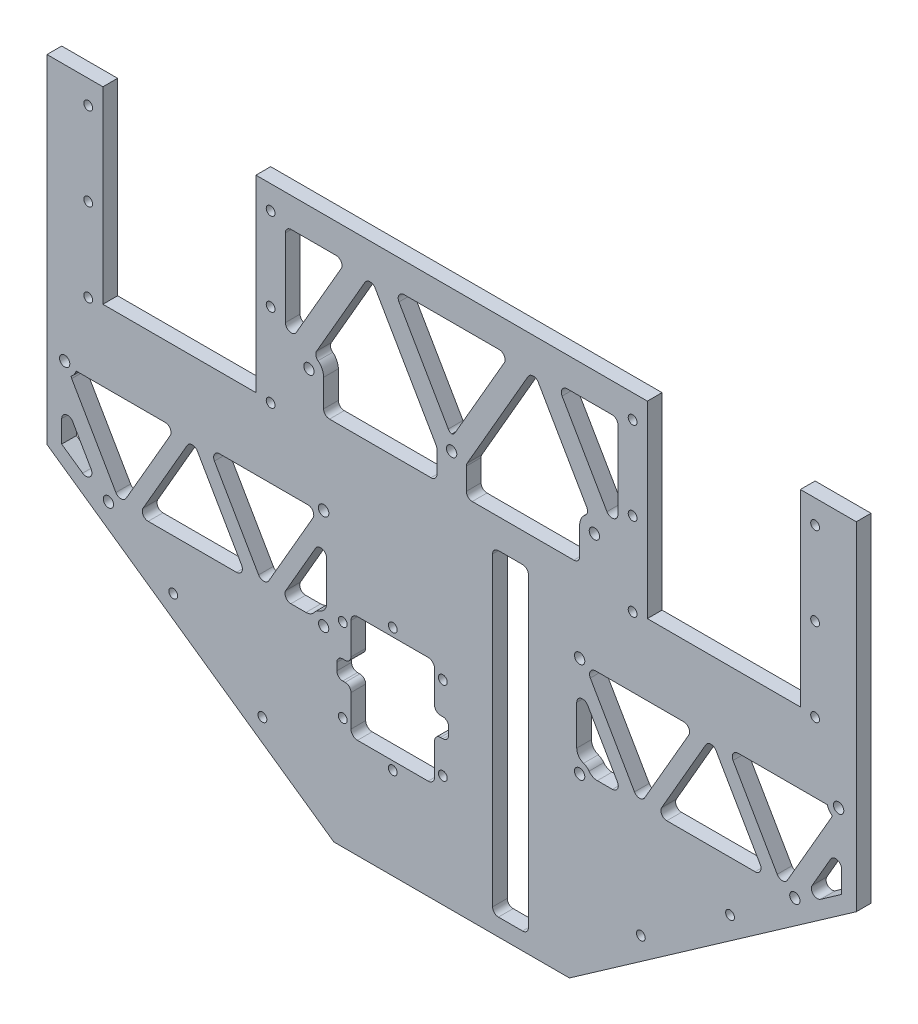
SolidWorks part; units mm, degrees
ref_plane "Front Plane" through (0, 0, 0) normal (0, 0, 1) x (1, 0, 0)
ref_plane "Top Plane" through (0, 0, 0) normal (0, 1, 0) x (1, 0, 0)
ref_plane "Right Plane" through (0, 0, 0) normal (1, 0, 0) x (0, 0, -1)
sketch "Model" plane through (0, 0, 0) normal (0, 0, 1) x (1, 0, 0)
  line L0 (25.9808, 54.5) -> (5.2679, 18.6244)
  line L1 (45.9002, 25.9986) -> (29.4449, 54.5)
  line L2 (43.5, 10.2107) -> (43.5, 19.5)
  line L3 (7, 8.2107) -> (41.5, 8.2107)
  line L4 (5, 10.2107) -> (5, 17.6244)
  line L5 (-56.5, 55.5) -> (-56.5, 29.1032)
  line L6 (-39.2598, 57.5) -> (-54.5, 57.5)
  line L7 (-52.7679, 28.1032) -> (-37.5278, 54.5)
  line L8 (-5, 10.2107) -> (-5, 17.6244)
  line L9 (-41.5, 8.2107) -> (-7, 8.2107)
  line L10 (-43.5, 10.2107) -> (-43.5, 19.5)
  line L11 (-45.9002, 25.9986) -> (-29.4449, 54.5)
  line L12 (-25.9808, 54.5) -> (-5.2679, 18.6244)
  line L13 (47.1188, -23.6806) -> (62.1299, -49.6806)
  line L14 (48.8509, -20.6806) -> (78.8731, -20.6806)
  line L15 (65.594, -49.6806) -> (80.6051, -23.6806)
  line L16 (49.5, -52.6806) -> (54.6244, -52.6806)
  line L17 (42.5, -46.6096) -> (42.5, -33.1447)
  line L18 (56.3564, -49.6806) -> (46.2321, -32.1447)
  line L19 (104.8538, -49.6806) -> (89.8427, -23.6806)
  line L20 (103.1218, -52.6806) -> (73.0996, -52.6806)
  line L21 (86.3786, -23.6806) -> (71.3675, -49.6806)
  line L22 (-71.3675, -49.6806) -> (-86.3786, -23.6806)
  line L23 (-103.1218, -52.6806) -> (-73.0996, -52.6806)
  line L24 (-104.8538, -49.6806) -> (-89.8427, -23.6806)
  line L25 (-110.6273, -49.6806) -> (-95.6162, -23.6806)
  line L26 (-129.1025, -23.6806) -> (-114.0914, -49.6806)
  line L27 (-97.3483, -20.6806) -> (-127.3705, -20.6806)
  line L28 (-42.5, -46.6096) -> (-42.5, -33.1447)
  line L29 (-54.6244, -52.6806) -> (-49.5, -52.6806)
  line L30 (-46.2321, -32.1447) -> (-56.3564, -49.6806)
  line L31 (-62.1299, -49.6806) -> (-47.1188, -23.6806)
  line L32 (-80.6051, -23.6806) -> (-65.594, -49.6806)
  line L33 (-48.8509, -20.6806) -> (-78.8731, -20.6806)
  line L34 (-122.5022, -47.0067) -> (-128.7679, -36.1541)
  line L35 (-132.5, -44.662) -> (-125.3812, -49.6451)
  line L36 (-132.5, -37.1541) -> (-132.5, -44.662)
  line L37 (122.5022, -47.0067) -> (128.7679, -36.1541)
  line L38 (132.5, -37.1541) -> (132.5, -44.662)
  line L39 (132.5, -44.662) -> (125.3812, -49.6451)
  line L40 (-3, -66.614) -> (-3.8, -66.614)
  line L41 (-5.8, -79.364) -> (-5.8, -68.614)
  line L42 (-32, -81.564) -> (-8, -81.564)
  line L43 (-34.2, -68.614) -> (-34.2, -79.364)
  line L44 (-37, -66.614) -> (-36.2, -66.614)
  line L45 (-39, -62.114) -> (-39, -64.614)
  line L46 (-36.2, -60.114) -> (-37, -60.114)
  line L47 (-34.2, -47.364) -> (-34.2, -58.114)
  line L48 (-8, -45.164) -> (-32, -45.164)
  line L49 (-5.8, -58.114) -> (-5.8, -47.364)
  line L50 (-3.8, -60.114) -> (-3, -60.114)
  line L51 (-1, -62.114) -> (-1, -64.614)
  line L52 (15.9, -109.6324) -> (24.1, -109.6324)
  line L53 (13.9, -3.7893) -> (13.9, -107.6324)
  line L54 (15.9, -1.7893) -> (24.1, -1.7893)
  line L55 (26.1, -3.7893) -> (26.1, -107.6324)
  line L56 (-66.5, 67.5) -> (66.5, 67.5)
  line L57 (-66.5, 67.5) -> (-66.5, 3.5)
  line L58 (-66.5, 3.5) -> (-118.5, 3.5)
  line L59 (-118.5, 3.5) -> (-118.5, 67.5)
  line L60 (-137.5, 67.5) -> (-118.5, 67.5)
  line L61 (-137.5, 67.5) -> (-137.5, -47.2652)
  line L62 (-137.5, -47.2652) -> (-40.0218, -115.5)
  line L63 (-40.0218, -115.5) -> (40.0218, -115.5)
  line L64 (40.0218, -115.5) -> (137.5, -47.2652)
  line L65 (137.5, 67.5) -> (137.5, -47.2652)
  line L66 (118.5, 67.5) -> (137.5, 67.5)
  line L67 (118.5, 3.5) -> (118.5, 67.5)
  line L68 (66.5, 3.5) -> (118.5, 3.5)
  line L69 (66.5, 3.5) -> (66.5, 67.5)
  line L70 (110.6273, -49.6806) -> (95.6162, -23.6806)
  line L71 (127.3705, -20.6806) -> (97.3483, -20.6806)
  line L72 (129.1025, -23.6806) -> (114.0914, -49.6806)
  line L73 (56.5, 55.5) -> (56.5, 29.1032)
  line L74 (52.7679, 28.1032) -> (37.5278, 54.5)
  line L75 (54.5, 57.5) -> (39.2598, 57.5)
  line L76 (1.1402, 25.4749) -> (17.8979, 54.5)
  line L77 (-1.1402, 25.4749) -> (-17.8979, 54.5)
  line L78 (16.1658, 57.5) -> (-16.1658, 57.5)
  circle A0 centre (-64.2915, -90.8821) radius 1.5
  circle A1 centre (-94.6031, -69.664) radius 1.5
  circle A2 centre (64.2915, -90.8821) radius 1.5
  circle A3 centre (94.6031, -69.664) radius 1.5
  circle A4 centre (48.5, 19.5) radius 1.75
  circle A5 centre (0, 19.5) radius 1.75
  circle A6 centre (-48.5, 19.5) radius 1.75
  arc A7 (29.4449, 54.5) -> (25.9808, 54.5) centre (27.7128, 53.5) ccw
  arc A8 (45.4058, 23.4276) -> (45.9002, 25.9986) centre (44.1681, 24.9986) ccw
  arc A9 (45.4058, 23.4276) -> (43.5, 19.5) centre (48.5, 19.5) ccw
  arc A10 (41.5, 8.2107) -> (43.5, 10.2107) centre (41.5, 10.2107) ccw
  arc A11 (5, 10.2107) -> (7, 8.2107) centre (7, 10.2107) ccw
  arc A12 (5.2679, 18.6244) -> (5, 17.6244) centre (7, 17.6244) ccw
  arc A13 (-54.5, 57.5) -> (-56.5, 55.5) centre (-54.5, 55.5) ccw
  arc A14 (-37.5278, 54.5) -> (-39.2598, 57.5) centre (-39.2598, 55.5) ccw
  arc A15 (-56.5, 29.1032) -> (-52.7679, 28.1032) centre (-54.5, 29.1032) ccw
  arc A16 (-7, 8.2107) -> (-5, 10.2107) centre (-7, 10.2107) ccw
  arc A17 (-43.5, 10.2107) -> (-41.5, 8.2107) centre (-41.5, 10.2107) ccw
  arc A18 (-43.5, 19.5) -> (-45.4058, 23.4276) centre (-48.5, 19.5) ccw
  arc A19 (-45.9002, 25.9986) -> (-45.4058, 23.4276) centre (-44.1681, 24.9986) ccw
  arc A20 (-25.9808, 54.5) -> (-29.4449, 54.5) centre (-27.7128, 53.5) ccw
  arc A21 (-5, 17.6244) -> (-5.2679, 18.6244) centre (-7, 17.6244) ccw
  circle A22 centre (131.5, -19.6806) radius 1.75
  circle A23 centre (-43.5, -53.6806) radius 1.75
  circle A24 centre (-131.5, -19.6806) radius 1.75
  circle A25 centre (-116.6209, -53.6806) radius 1.75
  circle A26 centre (116.6209, -53.6806) radius 1.75
  circle A27 centre (43.5, -19.6806) radius 1.75
  circle A28 centre (43.5, -53.6806) radius 1.75
  circle A29 centre (-43.5, -19.6806) radius 1.78
  arc A30 (62.1299, -49.6806) -> (65.594, -49.6806) centre (63.862, -48.6806) ccw
  arc A31 (48.8509, -20.6806) -> (47.1188, -23.6806) centre (48.8509, -22.6806) ccw
  arc A32 (80.6051, -23.6806) -> (78.8731, -20.6806) centre (78.8731, -22.6806) ccw
  arc A33 (54.6244, -52.6806) -> (56.3564, -49.6806) centre (54.6244, -50.6806) ccw
  arc A34 (46.7, -51.2806) -> (49.5, -52.6806) centre (49.5, -49.1806) ccw
  arc A35 (46.7, -51.2806) -> (44.8333, -49.9094) centre (43.5, -53.6806) ccw
  arc A36 (42.5, -46.6096) -> (44.8333, -49.9094) centre (46, -46.6096) ccw
  arc A37 (46.2321, -32.1447) -> (42.5, -33.1447) centre (44.5, -33.1447) ccw
  arc A38 (89.8427, -23.6806) -> (86.3786, -23.6806) centre (88.1107, -24.6806) ccw
  arc A39 (103.1218, -52.6806) -> (104.8538, -49.6806) centre (103.1218, -50.6806) ccw
  arc A40 (71.3675, -49.6806) -> (73.0996, -52.6806) centre (73.0996, -50.6806) ccw
  arc A41 (-86.3786, -23.6806) -> (-89.8427, -23.6806) centre (-88.1107, -24.6806) ccw
  arc A42 (-73.0996, -52.6806) -> (-71.3675, -49.6806) centre (-73.0996, -50.6806) ccw
  arc A43 (-104.8538, -49.6806) -> (-103.1218, -52.6806) centre (-103.1218, -50.6806) ccw
  arc A44 (-95.6162, -23.6806) -> (-97.3483, -20.6806) centre (-97.3483, -22.6806) ccw
  arc A45 (-114.0914, -49.6806) -> (-110.6273, -49.6806) centre (-112.3594, -48.6806) ccw
  arc A46 (-129.337, -23.0453) -> (-129.1025, -23.6806) centre (-127.3705, -22.6806) ccw
  arc A47 (-129.337, -23.0453) -> (-127.6315, -20.6977) centre (-131.5, -19.6806) ccw
  arc A48 (-127.3705, -20.6806) -> (-127.6315, -20.6977) centre (-127.3705, -22.6806) ccw
  arc A49 (-44.8333, -49.9094) -> (-42.5, -46.6096) centre (-46, -46.6096) ccw
  arc A50 (-44.8333, -49.9094) -> (-46.7, -51.2806) centre (-43.5, -53.6806) ccw
  arc A51 (-49.5, -52.6806) -> (-46.7, -51.2806) centre (-49.5, -49.1806) ccw
  arc A52 (-56.3564, -49.6806) -> (-54.6244, -52.6806) centre (-54.6244, -50.6806) ccw
  arc A53 (-42.5, -33.1447) -> (-46.2321, -32.1447) centre (-44.5, -33.1447) ccw
  arc A54 (-47.1188, -23.6806) -> (-48.8509, -20.6806) centre (-48.8509, -22.6806) ccw
  arc A55 (-65.594, -49.6806) -> (-62.1299, -49.6806) centre (-63.862, -48.6806) ccw
  arc A56 (-78.8731, -20.6806) -> (-80.6051, -23.6806) centre (-78.8731, -22.6806) ccw
  arc A57 (-125.3812, -49.6451) -> (-122.5022, -47.0067) centre (-124.2343, -48.0067) ccw
  arc A58 (-128.7679, -36.1541) -> (-132.5, -37.1541) centre (-130.5, -37.1541) ccw
  arc A59 (122.5022, -47.0067) -> (125.3812, -49.6451) centre (124.2343, -48.0067) ccw
  arc A60 (132.5, -37.1541) -> (128.7679, -36.1541) centre (130.5, -37.1541) ccw
  arc A61 (-3.8, -66.614) -> (-5.8, -68.614) centre (-3.8, -68.614) ccw
  arc A62 (-8, -81.564) -> (-5.8, -79.364) centre (-8, -79.364) ccw
  arc A63 (-34.2, -79.364) -> (-32, -81.564) centre (-32, -79.364) ccw
  arc A64 (-34.2, -68.614) -> (-36.2, -66.614) centre (-36.2, -68.614) ccw
  arc A65 (-39, -64.614) -> (-37, -66.614) centre (-37, -64.614) ccw
  arc A66 (-37, -60.114) -> (-39, -62.114) centre (-37, -62.114) ccw
  arc A67 (-36.2, -60.114) -> (-34.2, -58.114) centre (-36.2, -58.114) ccw
  arc A68 (-32, -45.164) -> (-34.2, -47.364) centre (-32, -47.364) ccw
  arc A69 (-5.8, -47.364) -> (-8, -45.164) centre (-8, -47.364) ccw
  arc A70 (-5.8, -58.114) -> (-3.8, -60.114) centre (-3.8, -58.114) ccw
  arc A71 (-1, -62.114) -> (-3, -60.114) centre (-3, -62.114) ccw
  arc A72 (-3, -66.614) -> (-1, -64.614) centre (-3, -64.614) ccw
  circle A73 centre (-20, -84.364) radius 1.5
  circle A74 centre (-3, -77.489) radius 1.5
  circle A75 centre (-3, -49.239) radius 1.5
  circle A76 centre (-20, -42.364) radius 1.5
  circle A77 centre (-37, -49.239) radius 1.5
  circle A78 centre (-37, -77.489) radius 1.5
  arc A79 (13.9, -107.6324) -> (15.9, -109.6324) centre (15.9, -107.6324) ccw
  arc A80 (15.9, -1.7893) -> (13.9, -3.7893) centre (15.9, -3.7893) ccw
  arc A81 (26.1, -3.7893) -> (24.1, -1.7893) centre (24.1, -3.7893) ccw
  arc A82 (24.1, -109.6324) -> (26.1, -107.6324) centre (24.1, -107.6324) ccw
  circle A83 centre (-61.5, 31.25) radius 1.5
  circle A84 centre (-61.5, 3) radius 1.5
  circle A85 centre (-123.5, 59.5) radius 1.5
  circle A86 centre (-123.5, 31.25) radius 1.5
  circle A87 centre (-123.5, 3) radius 1.5
  circle A88 centre (-61.5, 59.5) radius 1.5
  circle A89 centre (123.5, 31.25) radius 1.5
  circle A90 centre (123.5, 3) radius 1.5
  circle A91 centre (61.5, 59.5) radius 1.5
  circle A92 centre (61.5, 31.25) radius 1.5
  circle A93 centre (61.5, 3) radius 1.5
  circle A94 centre (123.5, 59.5) radius 1.5
  arc A95 (110.6273, -49.6806) -> (114.0914, -49.6806) centre (112.3594, -48.6806) ccw
  arc A96 (97.3483, -20.6806) -> (95.6162, -23.6806) centre (97.3483, -22.6806) ccw
  arc A97 (127.6315, -20.6977) -> (127.3705, -20.6806) centre (127.3705, -22.6806) ccw
  arc A98 (127.6315, -20.6977) -> (129.337, -23.0453) centre (131.5, -19.6806) ccw
  arc A99 (129.1025, -23.6806) -> (129.337, -23.0453) centre (127.3705, -22.6806) ccw
  arc A100 (52.7679, 28.1032) -> (56.5, 29.1032) centre (54.5, 29.1032) ccw
  arc A101 (39.2598, 57.5) -> (37.5278, 54.5) centre (39.2598, 55.5) ccw
  arc A102 (56.5, 55.5) -> (54.5, 57.5) centre (54.5, 55.5) ccw
  arc A103 (0, 24.5645) -> (1.1402, 25.4749) centre (-0.5918, 26.4749) ccw
  arc A104 (-1.1402, 25.4749) -> (0, 24.5645) centre (0.5918, 26.4749) ccw
  arc A105 (-16.1658, 57.5) -> (-17.8979, 54.5) centre (-16.1658, 55.5) ccw
  arc A106 (17.8979, 54.5) -> (16.1658, 57.5) centre (16.1658, 55.5) ccw
extrude "Boss-Extrude1" add sketch "Model" along normal blind 5
sketch "Sketch1" plane through (0, 0, 5) normal (0, 0, 1) x (1, 0, 0)
  line L0 (13.9, -3.7893) -> (13.9, -107.6324) construction
  line L1 (26.1, -107.6324) -> (26.1, -3.7893) construction
  line L2 (26.1, -107.6324) -> (26.1, -3.7893)
  line L3 (13.9, -3.7893) -> (13.9, -107.6324)
  point P0 (26.1, -3.7893)
  point P2 (13.9, -3.7893)
